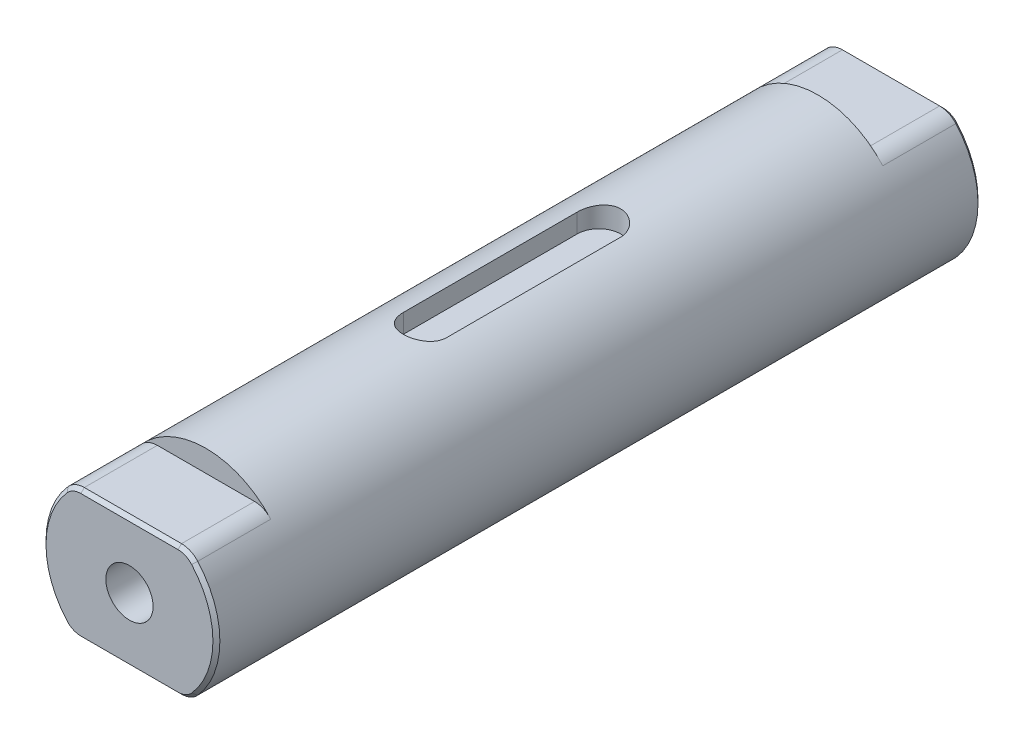
SolidWorks part; units mm, degrees
material "7075-T6, Plate (SS)"
ref_plane "Front Plane" through (0, 0, 0) normal (0, 0, 1) x (1, 0, 0)
ref_plane "Top Plane" through (0, 0, 0) normal (0, 1, 0) x (1, 0, 0)
ref_plane "Right Plane" through (0, 0, 0) normal (1, 0, 0) x (0, 0, -1)
sketch "Sketch1" plane through (0, 0, 0) normal (1, 0, 0) x (0, 0, -1)
  line L0 (0, 0) -> (50000, 0) construction
  line L1 (0, 0) -> (0, 6.35)
  line L6 (0, 6.35) -> (55.88, 6.35)
  line L7 (55.88, 6.35) -> (55.88, 0)
  line L8 (55.88, 0) -> (0, 0)
revolve "Revolve1" add sketch "Sketch1" angle 360 about L0
sketch "Sketch5" plane through (0, 0, 0) normal (0, 0, 1) x (1, 0, 0)
  line L0 (-4.2001, 4.7625) -> (4.2001, 4.7625)
  line L1 (-4.2001, -4.7625) -> (4.2001, -4.7625)
  line L2 (0, 4.7625) -> (0, -4.7625) construction
  arc A0 (-4.2001, -4.7625) -> (4.2001, -4.7625) centre (0, 0) ccw
  circle A1 centre (0, 0) radius 6.35 construction
  arc A2 (4.2001, 4.7625) -> (-4.2001, 4.7625) centre (0, 0) ccw
  point P11 (0, 0)
  dimension "D1" = 9.525
extrude "Cut-Extrude1" cut sketch "Sketch5" against normal blind 5.588
sketch "Sketch6" plane through (0, 0, -55.88) normal (0, 0, -1) x (-1, 0, 0)
  line L0 (-4.2001, 4.7625) -> (4.2001, 4.7625)
  line L1 (4.2001, -4.7625) -> (-4.2001, -4.7625)
  line L2 (0, 4.7625) -> (0, -4.7625) construction
  arc A0 (-4.2001, -4.7625) -> (4.2001, -4.7625) centre (0, 0) ccw
  arc A1 (4.2001, 4.7625) -> (-4.2001, 4.7625) centre (0, 0) ccw
  circle A2 centre (0, 0) radius 6.35 construction
  point P9 (0, 0)
  dimension "D1" = 9.525
extrude "Cut-Extrude2" cut sketch "Sketch6" against normal blind 5.588
hole_wizard "#8-32 Tapped Hole1" positions "Sketch8" profile "Sketch7" tap size "#8-32" standard "Ansi Inch"
sketch "Sketch8" plane through (0, 0, 0) normal (0, 0, 1) x (1, 0, 0)
  point P1 (0, 0)
sketch "Sketch7" plane through (0, 0, 0) normal (1, 0, 0) x (0, -1, 0)
  line L0 (0, 0) -> (0, 13.7378)
  line L1 (0, 13.7378) -> (1.7272, 12.7)
  line L2 (1.7272, 12.7) -> (1.7272, 0)
  line L5 (1.7272, 0) -> (0, 0)
  line L10 (0, 13.7378) -> (-1.7272, 12.7) construction
  line L11 (0, -6.35) -> (0, 107.95) construction
  dimension "Tap Drill Dia." = 3.4544
  dimension "Tap Drill Depth" = 12.7
  dimension "Drill Angle" = 118
cosmetic thread "Hole Thread2" parameters "D1"=8.382, "D2"=4.1656
hole_wizard "#8-32 Tapped Hole2" positions "Sketch10" profile "Sketch9" tap size "#8-32" standard "Ansi Inch"
sketch "Sketch10" plane through (0, 0, -55.88) normal (0, 0, -1) x (-1, 0, 0)
  point P1 (0, 0)
sketch "Sketch9" plane through (0, 0, -55.88) normal (1, 0, 0) x (0, 1, 0)
  line L0 (0, 0) -> (0, 13.7378)
  line L1 (0, 13.7378) -> (1.7272, 12.7)
  line L2 (1.7272, 12.7) -> (1.7272, 0)
  line L5 (1.7272, 0) -> (0, 0)
  line L10 (0, 13.7378) -> (-1.7272, 12.7) construction
  line L11 (0, -6.35) -> (0, 107.95) construction
  dimension "Tap Drill Dia." = 3.4544
  dimension "Tap Drill Depth" = 12.7
  dimension "Drill Angle" = 118
cosmetic thread "Hole Thread3" parameters "D1"=8.382, "D2"=4.1656
fillet "Fillet1" radius 1.5875 8 edges at (4.2001, -4.7625, -53.086) (-4.2001, -4.7625, -53.086) (4.2001, 4.7625, -53.086) (-4.2001, 4.7625, -53.086) (-4.2001, -4.7625, -2.794) (4.2001, -4.7625, -2.794) (-4.2001, 4.7625, -2.794) (4.2001, 4.7625, -2.794)
chamfer "Chamfer1" distance 0.254 angle 45 16 edges at (0, -4.7625, -55.88) (4.1979, -4.6242, -55.88) (-4.1979, -4.6242, -55.88) (6.35, 0, -55.88) (-6.35, 0, -55.88) (4.1979, 4.6242, -55.88) (-4.1979, 4.6242, -55.88) (0, 4.7625, -55.88) (0, -4.7625, 0) (0, 4.7625, 0) (-4.1979, -4.6242, 0) (4.1979, -4.6242, 0) (-6.35, 0, 0) (6.35, 0, 0) (-4.1979, 4.6242, 0) (4.1979, 4.6242, 0)
ref_plane "Plane1" through (0, 6.35, 0) normal (0, 1, 0) x (-1, 0, 0)
sketch "Sketch11" plane through (0, 6.35, 0) normal (0, 1, 0) x (-1, 0, 0)
  line L0 (0, -34.29) -> (0, -21.59) construction
  line L1 (-1.5875, -34.29) -> (-1.5875, -21.59)
  line L2 (1.5875, -34.29) -> (1.5875, -21.59)
  line L4 (6.35, -27.94) -> (-6.35, -27.94) construction
  line L5 (6.35, -55.626) -> (6.35, -0.254) construction
  line L6 (-6.35, -0.254) -> (-6.35, -55.626) construction
  arc A0 (-1.5875, -34.29) -> (1.5875, -34.29) centre (0, -34.29) ccw
  arc A1 (1.5875, -21.59) -> (-1.5875, -21.59) centre (0, -21.59) ccw
  point P2 (0, -27.94)
  dimension "D1" = 3.175
  dimension "D3" = 12.7
extrude "Cut-Extrude3" cut sketch "Sketch11" against normal blind 1.5875
